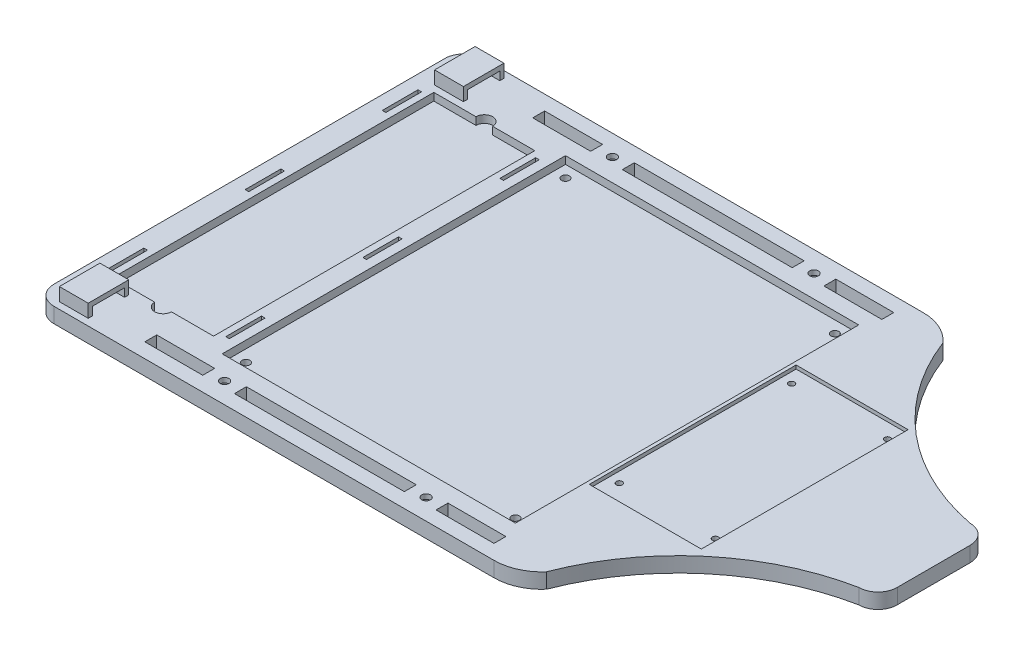
SolidWorks part; units mm, degrees
ref_plane "Alzado" through (0, 0, 0) normal (0, 0, 1) x (1, 0, 0)
ref_plane "Planta" through (0, 0, 0) normal (0, 1, 0) x (1, 0, 0)
ref_plane "Vista lateral" through (0, 0, 0) normal (1, 0, 0) x (0, 0, -1)
sketch "Croquis1" plane through (0, 0, 0) normal (0, 1, 0) x (1, 0, 0)
  line L1 (-363.842, 247.1559) -> (108.158, 247.1559) construction
  line L2 (98.4842, 266.9705) -> (494.4842, 266.9705) construction
  line L11 (99, 267.5) -> (495, 267.5) construction
  line L12 (0, 0) -> (200, 0)
  line L22 (0, 90) -> (105.7, 90)
  line L23 (105.7, 90) -> (105.7, 83.1308) construction
  line L24 (105.7, 83.1308) -> (120.7782, 83.1308) construction
  line L25 (200, 0) -> (200, 15.2)
  line L26 (200, 15.2) -> (191.999, 15.2) construction
  line L27 (191.999, 15.2) -> (191.999, 23.325) construction
  line L29 (0, 0) -> (-110.4, 0)
  line L30 (0, 90) -> (-79, 90)
  line L31 (-110.4, 0) -> (-110.4, 13.12)
  line L32 (-86.9998, 82.0528) -> (-86.9998, 41.494)
  arc A0 (105.7, 90) -> (120.7782, 83.1308) centre (105.672, 69.9553) cw
  arc A1 (200, 15.2) -> (191.999, 23.325) centre (192.001, 15.325) ccw
  arc A2 (120.7782, 83.1308) -> (191.999, 23.325) centre (210.4273, 117.5809) ccw
  arc A3 (-79, 90) -> (-86.9998, 82.0528) centre (-79, 82) ccw
  arc A4 (-110.4, 13.12) -> (-102.3535, 21.1199) centre (-102.4, 13.12) cw
  arc A5 (-102.3535, 21.1199) -> (-86.9998, 41.494) centre (-113.1395, 45.2203) ccw
  dimension "D6" = 20.0447
  dimension "D10" = 8
  dimension "D11" = 96.0405
  dimension "D15" = 8
  dimension "D17" = 8
  dimension "D19" = 26.4039
  dimension "D22" = 45.2203
  dimension "D1" = 90
  dimension "D2" = 200
  dimension "D3" = 105.7
  dimension "D4" = 6.8692
  dimension "D5" = 15.0782
  dimension "D7" = 15.2
  dimension "D8" = 8.001
  dimension "D9" = 8.125
  dimension "D12" = 105.7
  dimension "D13" = 310.4
  dimension "D14" = 79
  dimension "D16" = 13.12
  dimension "D18" = 40.5588
  dimension "D20" = 90
  dimension "D21" = 286.9998
extrude "Saliente-Extruir1" add sketch "Croquis1" along normal blind 6.35
mirror "Simetría2" about plane through (0, 6.35, 0) normal (0, 0, -1) of bodies 104
sketch "Croquis2" plane through (0, 6.35, 0) normal (0, 1, 0) x (1, 0, 0)
  line L0 (200, 0) -> (-110.4, 0) construction
  line L1 (200, -15.2) -> (200, 15.2) construction
  line L2 (-110.4, 13.12) -> (-110.4, -13.12) construction
  line L3 (0, 90) -> (-86.9348, 90) construction
  line L4 (105.7, 90) -> (-79, 90) construction
  line L5 (-17.875, 81.35) -> (70.325, 81.35) construction
  line L6 (0, 90) -> (0, 0) construction
  line L7 (-14.225, 81.35) -> (-1.9998, 81.35) construction
  line L8 (13.35, -90) -> (13.35, 90) construction
  line L9 (105.7, -90) -> (-79, -90) construction
  line L10 (-17.875, -81.35) -> (70.325, -81.35) construction
  line L15 (26.225, -81.35) -> (26.225, -54.2886) construction
  line L16 (-1.9998, -83.85) -> (61.85, -83.85)
  line L17 (-1.9998, -83.85) -> (-1.9998, -78.85)
  line L18 (-1.9998, -78.85) -> (61.85, -78.85)
  line L19 (61.85, -83.85) -> (61.85, -78.85)
  line L20 (-86.9998, -82.0528) -> (-86.9998, -41.494) construction
  line L21 (-46.9998, -78.85) -> (-22.7, -78.85)
  line L22 (-46.9998, -78.85) -> (-46.9998, -83.85)
  line L23 (-46.9998, -83.85) -> (-22.7, -83.85)
  line L24 (-22.7, -78.85) -> (-22.7, -83.85)
  line L25 (99.4498, -83.85) -> (75.15, -83.85)
  line L26 (75.15, -78.85) -> (75.15, -83.85)
  line L27 (99.4498, -78.85) -> (75.15, -78.85)
  line L28 (99.4498, -78.85) -> (99.4498, -83.85)
  line L29 (-46.9998, 83.85) -> (-22.7, 83.85)
  line L30 (-22.7, 78.85) -> (-22.7, 83.85)
  line L31 (-46.9998, 78.85) -> (-22.7, 78.85)
  line L32 (-46.9998, 78.85) -> (-46.9998, 83.85)
  line L33 (-1.9998, 78.85) -> (61.85, 78.85)
  line L34 (61.85, 83.85) -> (61.85, 78.85)
  line L35 (-1.9998, 83.85) -> (61.85, 83.85)
  line L36 (-1.9998, 83.85) -> (-1.9998, 78.85)
  line L37 (99.4498, 78.85) -> (99.4498, 83.85)
  line L38 (99.4498, 78.85) -> (75.15, 78.85)
  line L39 (75.15, 78.85) -> (75.15, 83.85)
  line L40 (99.4498, 83.85) -> (75.15, 83.85)
  circle A0 centre (68.5, 81.35) radius 1.825
  circle A1 centre (-16.05, 81.35) radius 1.825
  circle A2 centre (68.5, -81.35) radius 1.825
  circle A3 centre (-16.05, -81.35) radius 1.825
  point P33 (-1.9998, -81.35)
  point P41 (-22.7, -81.35)
  dimension "3.6" = 3.65
  dimension "D5" = 3.65
  dimension "D10" = 84.55
  dimension "D17" = 4.825
  dimension "D2" = 81.35
  dimension "D3" = 110.4
  dimension "D4" = 68.5
  dimension "D6" = 88.2
  dimension "D7" = 63.8498
  dimension "D8" = 6.65
  dimension "D9" = 5
  dimension "D11" = 14.0502
  dimension "D12" = 6.65
  dimension "D13" = 5
  dimension "D14" = 40
  dimension "D15" = 90
  dimension "D16" = 90
  dimension "D18" = 88.2
extrude "Cortar-Extruir1" cut sketch "Croquis2" against normal through all
sketch "Croquis3" plane through (0, 6.35, 0) normal (0, 1, 0) x (1, 0, 0)
  line L0 (200, 0) -> (-110.4, 0) construction
  line L1 (200, -15.2) -> (200, 15.2) construction
  line L2 (-110.4, 13.12) -> (-110.4, -13.12) construction
  line L3 (-86.9998, 82.0528) -> (-86.9998, 41.494) construction
  line L4 (-76.9998, 67.375) -> (-59.3248, 67.375)
  line L5 (-76.9998, 67.375) -> (-76.9998, -67.375)
  line L6 (-76.9998, -67.375) -> (-59.3248, -67.375)
  line L7 (-34.6498, 67.375) -> (-34.6498, -67.375)
  line L10 (-52.3248, 67.375) -> (-34.6498, 67.375)
  line L11 (-52.3248, -67.375) -> (-34.6498, -67.375)
  arc A0 (-59.3248, -67.375) -> (-52.3248, -67.375) centre (-55.8248, -67.375) ccw
  arc A1 (-59.3248, 67.375) -> (-52.3248, 67.375) centre (-55.8248, 67.375) cw
  point P10 (-34.6498, 0)
  dimension "D5" = 3.5
  dimension "D6" = 21.175
  dimension "D1" = 134.75
  dimension "D2" = 42.35
  dimension "D3" = 10
  dimension "D4" = 7
extrude "Cortar-Extruir2" cut sketch "Croquis3" against normal blind 3.175
sketch "Croquis4" plane through (0, 6.35, 0) normal (0, 1, 0) x (1, 0, 0)
  line L0 (200, 0) -> (-110.4, 0) construction
  line L1 (200, -15.2) -> (200, 15.2) construction
  line L2 (-110.4, 13.12) -> (-110.4, -13.12) construction
  line L4 (100, 40.425) -> (145, 40.425)
  line L5 (100, 40.425) -> (100, -40.425)
  line L6 (100, -40.425) -> (145, -40.425)
  line L7 (145, 40.425) -> (145, -40.425)
  point P10 (145, 0)
  dimension "D1" = 80.85
  dimension "D2" = 45
  dimension "D3" = 55
extrude "Cortar-Extruir3" cut sketch "Croquis4" against normal blind 1.5
sketch "Croquis5" plane through (0, 4.85, 0) normal (0, 1, 0) x (1, 0, 0)
  line L0 (122.5, 40.425) -> (122.5, -40.425) construction
  line L1 (145, 40.425) -> (100, 40.425) construction
  line L2 (100, -40.425) -> (145, -40.425) construction
  line L3 (100, 0) -> (145, 0) construction
  line L4 (100, 40.425) -> (100, -40.425) construction
  line L5 (145, -40.425) -> (145, 40.425) construction
  line L6 (143.9, -34.175) -> (145, -34.175) construction
  line L7 (145, -40.425) -> (145, 40.425) construction
  line L8 (142.65, -35.425) -> (142.65, -40.425) construction
  line L9 (100, -40.425) -> (145, -40.425) construction
  line L10 (143.9, 38.075) -> (145, 38.075) construction
  line L11 (142.65, 39.325) -> (142.65, 40.425) construction
  line L12 (145, 40.425) -> (100, 40.425) construction
  circle A0 centre (142.65, -34.175) radius 1.25
  circle A1 centre (102.35, -34.175) radius 1.25
  circle A2 centre (142.65, 38.075) radius 1.25
  circle A3 centre (102.35, 38.075) radius 1.25
  dimension "D1" = 2.5
  dimension "D4" = 2.5
  dimension "D2" = 1.1
  dimension "D3" = 5
  dimension "D5" = 1.1
  dimension "D6" = 1.1
extrude "Cortar-Extruir4" cut sketch "Croquis5" against normal through all
sketch "Croquis7" plane through (0, 6.35, 0) normal (0, 1, 0) x (1, 0, 0)
  line L0 (102.35, -35.425) -> (102.35, -40.425) construction
  line L1 (100, -40.425) -> (145, -40.425) construction
  line L2 (102.35, 39.325) -> (102.35, 44.325) construction
  line L3 (100, 40.425) -> (144.9959, 40.425)
  line L4 (100, 40.425) -> (100, 44.325)
  line L5 (100, 44.325) -> (144.9959, 44.325)
  line L6 (144.9959, 40.425) -> (144.9959, 44.325)
  circle A0 centre (102.35, -34.175) radius 1.25 construction
  circle A1 centre (102.35, 38.075) radius 1.25 construction
  dimension "D1" = 5
  dimension "D2" = 5
extrude "Cortar-Extruir5" cut sketch "Croquis7" against normal up to surface (1.5 mm away) up to face at (102.35, 4.85, 32.925)
sketch "Croquis8" plane through (0, 6.35, 0) normal (0, 1, 0) x (1, 0, 0)
  line L0 (-76.9998, 67.375) -> (-76.9998, -67.375) construction
  line L3 (-80.4998, 57.4058) -> (-80.4998, -89.8582) construction
  line L4 (-110.4, 0) -> (-34.6498, 0) construction
  line L5 (-110.4, 13.12) -> (-110.4, -13.12) construction
  line L6 (-55.8248, 70.875) -> (-55.8248, -70.875) construction
  line L7 (-81.2498, -50) -> (-79.7498, -50)
  line L8 (-81.2498, 65) -> (-79.7498, 65)
  line L9 (-81.2498, 65) -> (-81.2498, 50)
  line L10 (-81.2498, 50) -> (-79.7498, 50)
  line L11 (-79.7498, 65) -> (-79.7498, 50)
  line L12 (-79.7498, -65) -> (-79.7498, -50)
  line L13 (-81.2498, -65) -> (-79.7498, -65)
  line L14 (-81.2498, -65) -> (-81.2498, -50)
  line L15 (-30.3998, -65) -> (-30.3998, -50)
  line L16 (-79.7498, 7.5) -> (-81.2498, 7.5)
  line L17 (-79.7498, 7.5) -> (-79.7498, -7.5)
  line L18 (-79.7498, -7.5) -> (-81.2498, -7.5)
  line L19 (-81.2498, 7.5) -> (-81.2498, -7.5)
  line L20 (-30.3998, -65) -> (-31.8998, -65)
  line L21 (-31.8998, -65) -> (-31.8998, -50)
  line L22 (-30.3998, -50) -> (-31.8998, -50)
  line L23 (-31.8998, -7.5) -> (-30.3998, -7.5)
  line L24 (-30.3998, 7.5) -> (-30.3998, -7.5)
  line L25 (-31.8998, 7.5) -> (-30.3998, 7.5)
  line L26 (-31.8998, 7.5) -> (-31.8998, -7.5)
  line L27 (-30.3998, 50) -> (-31.8998, 50)
  line L28 (-31.8998, 65) -> (-31.8998, 50)
  line L29 (-30.3998, 65) -> (-31.8998, 65)
  line L30 (-30.3998, 65) -> (-30.3998, 50)
  arc A0 (-86.9998, -82.0528) -> (-79, -90) centre (-79, -82) ccw construction
  arc A1 (-52.3248, 67.375) -> (-59.3248, 67.375) centre (-55.8248, 67.375) ccw construction
  arc A2 (-59.3248, -67.375) -> (-52.3248, -67.375) centre (-55.8248, -67.375) ccw construction
  point P28 (-80.4998, 65)
  point P29 (-80.4998, 50)
  point P38 (-81.2498, 0)
  point P39 (-80.4998, 7.5)
  dimension "D1" = 50
  dimension "D2" = 1.5
  dimension "D3" = 15
  dimension "D4" = 15
  dimension "D5" = 1.5
  dimension "D6" = 3.5
extrude "Cortar-Extruir6" cut sketch "Croquis8" against normal through all
sketch "Croquis9" plane through (0, 6.35, 0) normal (0, 1, 0) x (1, 0, 0)
  line L0 (-110.4, 0) -> (200, 0) construction
  line L1 (-110.4, 13.12) -> (-110.4, -13.12) construction
  line L2 (200, -15.2) -> (200, 15.2) construction
  line L4 (-26.3998, 72) -> (96.6002, 72)
  line L5 (-26.3998, 72) -> (-26.3998, -72)
  line L6 (-26.3998, -72) -> (96.6002, -72)
  line L7 (96.6002, 72) -> (96.6002, -72)
  line L10 (-30.3998, -7.5) -> (-30.3998, 7.5) construction
  point P10 (96.6002, 0)
  dimension "D1" = 123
  dimension "D2" = 144
  dimension "D3" = 4
extrude "Cortar-Extruir7" cut sketch "Croquis9" against normal blind 3.175
sketch "Croquis10" plane through (0, 0, 0) normal (0, -1, 0) x (1, 0, 0)
  line L0 (200, 0) -> (-110.4, 0) construction
  line L1 (200, 15.2) -> (200, -15.2) construction
  line L2 (-110.4, -13.12) -> (-110.4, 13.12) construction
  line L3 (105.7, 90) -> (-79, 90) construction
  line L4 (29.9251, 90) -> (29.9251, 0) construction
  line L5 (-16.05, 81.35) -> (68.5, 81.35) construction
  line L6 (26.225, 81.35) -> (26.225, 0) construction
  circle A0 centre (-16.05, 81.35) radius 2.8
  circle A3 centre (-16.05, -81.35) radius 2.8
  circle A4 centre (68.5, -81.35) radius 2.8
  circle A5 centre (68.5, 81.35) radius 2.8
  dimension "D3" = 5.6
  dimension "D1" = 90
  dimension "D2" = 170.0749
extrude "Cortar-Extruir8" cut sketch "Croquis10" against normal blind 4.35
sketch "Croquis11" plane through (0, 3.175, 0) normal (0, 1, 0) x (1, 0, 0)
  line L0 (35.1002, 72) -> (35.1002, -72) construction
  line L1 (96.6002, 72) -> (-26.3998, 72) construction
  line L2 (-26.3998, -72) -> (96.6002, -72) construction
  line L3 (-26.3998, 0) -> (96.6002, 0) construction
  line L4 (-26.3998, 72) -> (-26.3998, -72) construction
  line L5 (96.6002, -72) -> (96.6002, 72) construction
  line L8 (-26.3998, -72) -> (96.6002, -72) construction
  line L9 (-24.3998, 70) -> (94.6002, 70) construction
  line L10 (-24.3998, 70) -> (-24.3998, -70) construction
  line L11 (-24.3998, -70) -> (94.6002, -70) construction
  line L12 (94.6002, 70) -> (94.6002, -70) construction
  circle A0 centre (-21.3998, 67) radius 1.65
  circle A1 centre (91.6002, 67) radius 1.65
  circle A2 centre (91.6002, -67) radius 1.65
  circle A3 centre (-21.3998, -67) radius 1.65
  dimension "D1" = 3.3
  dimension "D2" = 3
  dimension "D3" = 3
  dimension "D4" = 2
  dimension "D5" = 2
  dimension "D6" = 2
  dimension "D7" = 2
  dimension "D8" = 119
  dimension "D9" = 140
extrude "Cortar-Extruir9" cut sketch "Croquis11" against normal through all
sketch "Croquis13" plane through (0, 6.35, 0) normal (0, 1, 0) x (1, 0, 0)
  line L0 (-76.9998, -67.375) -> (-59.3248, -67.375) construction
  line L1 (-76.9998, -67.375) -> (-59.3248, -67.375) construction
  line L2 (-79.4998, 70.1875) -> (-79.4998, 87.1875)
  line L3 (-110.4, 0) -> (-26.3998, 0) construction
  line L4 (-110.4, 13.12) -> (-110.4, -13.12) construction
  line L5 (-26.3998, 72) -> (-26.3998, -72) construction
  line L6 (-68.1623, -78.6875) -> (-86.9998, -78.6875) construction
  line L7 (-86.9998, -82.0528) -> (-86.9998, -41.494) construction
  line L8 (-68.1623, -67.375) -> (-68.1623, -78.6875) construction
  line L9 (-68.1623, -73.0312) -> (-86.9998, -73.0312) construction
  line L10 (-67.3998, -70.1875) -> (-67.3998, -87.1875)
  line L11 (-67.3998, -70.1875) -> (-79.4998, -70.1875)
  line L12 (-79.4998, -70.1875) -> (-79.4998, -87.1875)
  line L13 (-79.4998, -87.1875) -> (-67.3998, -87.1875)
  line L15 (-67.3998, 70.1875) -> (-79.4998, 70.1875)
  line L16 (-67.3998, 70.1875) -> (-67.3998, 87.1875)
  line L17 (-79.4998, 87.1875) -> (-67.3998, 87.1875)
  point P21 (-67.3998, -78.6875)
  dimension "D1" = 17
  dimension "D2" = 11.3125
  dimension "D3" = 2.8125
  dimension "D4" = 12.1
  dimension "D5" = 7.5
extrude "Saliente-Extruir2" add sketch "Croquis13" along normal blind 5.5
sketch "Croquis14" plane through (-79.4998, 0, 0) normal (-1, 0, 0) x (0, 0, 1)
  line L0 (78.6875, 11.85) -> (78.6875, 6.35) construction
  line L1 (70.1875, 11.85) -> (87.1875, 11.85) construction
  line L2 (70.1875, 6.35) -> (87.1875, 6.35) construction
  line L8 (82.0528, 6.35) -> (41.494, 6.35) construction
  line L9 (71.9375, 9.85) -> (85.4375, 9.85)
  line L10 (71.9375, 9.85) -> (71.9375, 6.35)
  line L11 (71.9375, 6.35) -> (85.4375, 6.35)
  line L12 (85.4375, 9.85) -> (85.4375, 6.35)
  point P10 (78.6875, 9.85)
  dimension "D1" = 3.5
  dimension "D2" = 13.5
  dimension "D3" = 90
extrude "Cortar-Extruir10" cut sketch "Croquis14" against normal up to surface (12.1 mm away) up to face at (-67.3998, 9.1, 78.6875)
sketch "Croquis15" plane through (-79.4998, 0, 0) normal (-1, 0, 0) x (0, 0, 1)
  line L0 (-78.6875, 11.85) -> (-78.6875, 6.35) construction
  line L1 (-87.1875, 11.85) -> (-70.1875, 11.85) construction
  line L2 (-87.1875, 6.35) -> (-70.1875, 6.35) construction
  line L4 (-85.4375, 6.35) -> (-71.9375, 6.35)
  line L5 (-85.4375, 6.35) -> (-85.4375, 9.85)
  line L6 (-85.4375, 9.85) -> (-71.9375, 9.85)
  line L7 (-71.9375, 6.35) -> (-71.9375, 9.85)
  point P10 (-78.6875, 9.85)
  dimension "D1" = 3.5
  dimension "D2" = 13.5
  dimension "D3" = 90
extrude "Cortar-Extruir11" cut sketch "Croquis15" against normal up to surface (12.1 mm away) up to face at (-67.3998, 9.1, -78.6875)
sketch "Croquis16" plane through (0, 6.35, 0) normal (0, 1, 0) x (1, 0, 0)
  line L0 (-86.9998, 41.494) -> (-110.4, 41.494)
  line L1 (-110.4, 41.494) -> (-110.4, 13.12)
  line L2 (-110.4, 13.12) -> (-110.4, -13.12)
  line L3 (-110.4, -13.12) -> (-110.4, -41.494)
  line L4 (-110.4, -41.494) -> (-86.9998, -41.494)
  line L5 (-86.9998, -41.494) -> (-86.9998, 41.494)
  point P10 (0, 0)
extrude "Cortar-Extruir12" cut sketch "Croquis16" against normal through all
sketch "Croquis18" plane through (0, 6.35, 0) normal (0, 1, 0) x (1, 0, 0)
  line L0 (100, 44.325) -> (98, 44.325)
  line L1 (98, 44.325) -> (98, -42.425)
  line L2 (98, -42.425) -> (144.9959, -42.425)
  line L3 (144.9959, -42.425) -> (145, -40.425)
  line L4 (145, -40.425) -> (100, -40.425)
  line L5 (100, -40.425) -> (100, 44.325)
  dimension "D1" = 2
  dimension "D2" = 2
extrude "Cortar-Extruir15" cut sketch "Croquis18" against normal up to surface (1.5 mm away) up to face at (102.35, 4.85, 32.925)
sketch "Croquis19" plane through (0, 6.35, 0) normal (0, 1, 0) x (1, 0, 0)
  line L0 (200, 0) -> (-86.9998, 0) construction
  line L1 (200, -15.2) -> (200, 15.2) construction
  line L2 (-86.9998, 82.0528) -> (-86.9998, -82.0528) construction
  line L3 (-17.875, 81.35) -> (-22.7, 81.35) construction
  line L4 (-22.7, 78.85) -> (-22.7, 83.85) construction
  line L5 (-9.395, 81.35) -> (-14.225, 81.35) construction
  line L6 (-1.9998, 83.85) -> (-9.395, 83.85)
  line L7 (-1.9998, 83.85) -> (-1.9998, 78.85)
  line L8 (-1.9998, 78.85) -> (-9.395, 78.85)
  line L9 (-9.395, 83.85) -> (-9.395, 78.85)
  line L10 (-1.9998, -78.85) -> (-9.395, -78.85)
  line L11 (-9.395, -83.85) -> (-9.395, -78.85)
  line L12 (-1.9998, -83.85) -> (-9.395, -83.85)
  line L13 (-1.9998, -83.85) -> (-1.9998, -78.85)
  circle A0 centre (-16.05, 81.35) radius 1.825 construction
  dimension "D1" = 4.83
extrude "Cortar-Extruir16" cut sketch "Croquis19" against normal through all
